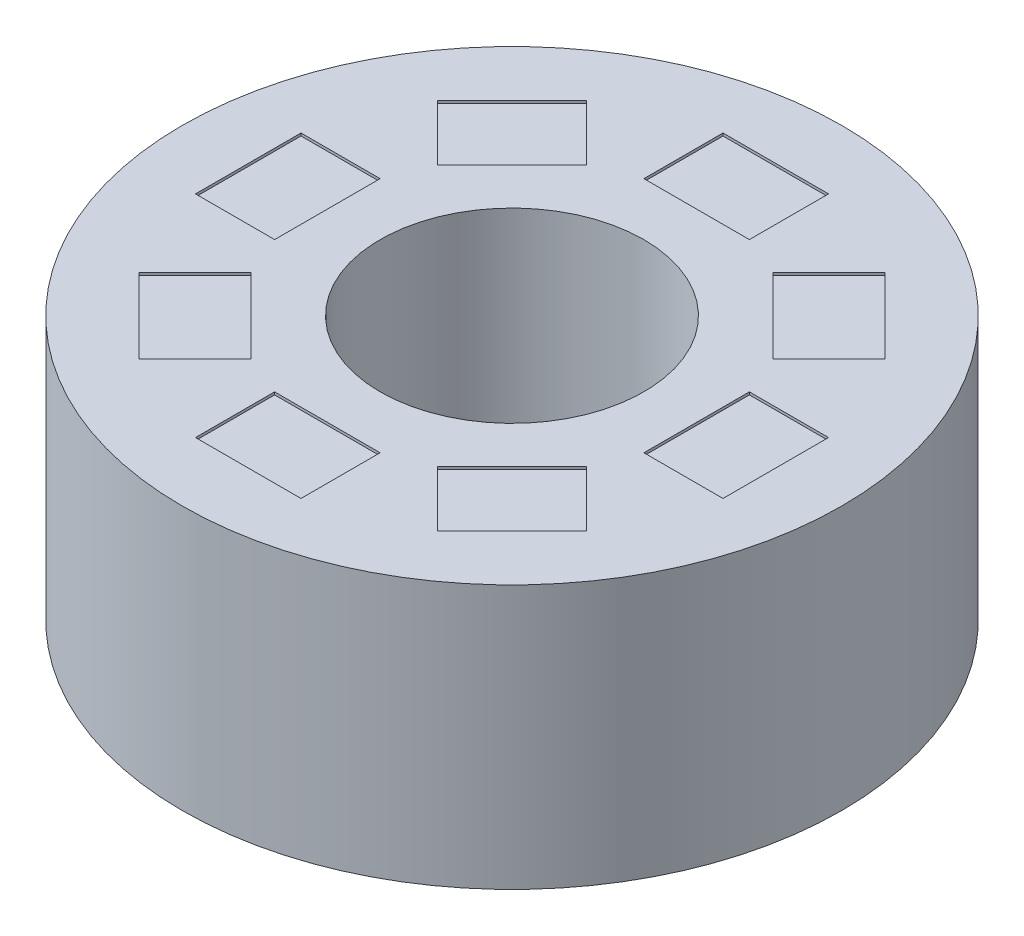
SolidWorks part; units mm, degrees
material "Nylon 6/10"
ref_plane "Front Plane" through (0, 0, 0) normal (0, 0, 1) x (1, 0, 0)
ref_plane "Top Plane" through (0, 0, 0) normal (0, 1, 0) x (1, 0, 0)
ref_plane "Right Plane" through (0, 0, 0) normal (1, 0, 0) x (0, 0, -1)
sketch "Sketch1" plane through (0, 0, 0) normal (0, 1, 0) x (1, 0, 0)
  circle A0 centre (0, 0) radius 125
  circle A1 centre (0, 0) radius 50
  dimension "D1" = 250
  dimension "D2" = 100
extrude "Boss-Extrude1" add sketch "Sketch1" along normal mid plane 100
sketch "Sketch2" plane through (0, 50, 0) normal (0, 1, 0) x (1, 0, 0)
  line L0 (0, -1000) -> (0, 49000) construction
  line L1 (-1000, 0) -> (49000, 0) construction
  line L3 (-20, 100) -> (20, 100)
  line L4 (-20, 100) -> (-20, 70)
  line L5 (-20, 70) -> (20, 70)
  line L6 (20, 100) -> (20, 70)
  line L7 (-20, 100) -> (20, 70) construction
  line L8 (-20, 70) -> (20, 100) construction
  point P4 (0, 85)
  dimension "D1" = 30
  dimension "D2" = 40
  dimension "D3" = 85
extrude "Cut-Extrude1" cut sketch "Sketch2" against normal blind 1
pattern_circular "CirPattern1" count 8 over 360 about axis through (0, 0, 0) along (0, 1, 0) of "Cut-Extrude1"
